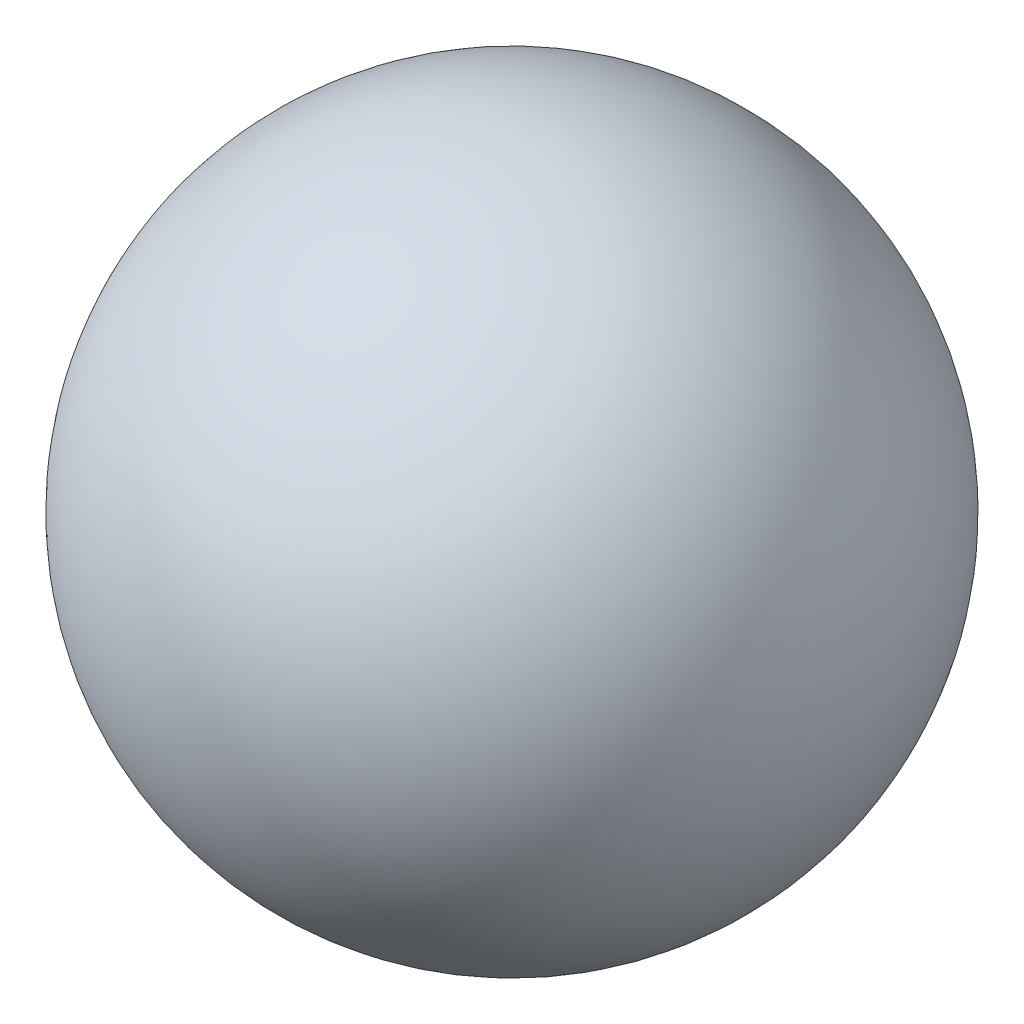
SolidWorks part; units mm, degrees
ref_plane "Front Plane" through (0, 0, 0) normal (0, 0, 1) x (1, 0, 0)
ref_plane "Top Plane" through (0, 0, 0) normal (0, 1, 0) x (1, 0, 0)
ref_plane "Right Plane" through (0, 0, 0) normal (1, 0, 0) x (0, 0, -1)
sketch "Sketch1" plane through (0, 0, 0) normal (0, 0, 1) x (1, 0, 0)
  line L0 (-19.939, 0) -> (19.939, 0) construction
  line L1 (19.939, 0) -> (-19.939, 0)
  arc A1 (19.939, 0) -> (-19.939, 0) centre (0, 0) ccw
  dimension "D1" = 19.939
revolve "Revolve7" add sketch "Sketch1" angle 360 about L0
equation "\"FoamCore\" = \".2\""
equation "\"MDF\" = \".2\""
equation "\"GMaterial\"= \".2\""
equation "\"PVCMountDiameter\" = \"0.5in\""
equation "\"PVCMountDistanceToEdge\" = \"0.5\""
equation "\"PVCThickness\" = \"0.13in\""
equation "\"BaseWidth\" = \"8in\""
equation "\"BaseLength\" = \"10in\""
equation "\"BallDiameter\" = \"1.57in\""
equation "\"BaseGap\" = \"4in\""
equation "\"FunnelTopDiameter\" = \"8in\""
equation "\"FunnelTopDepth\" = \"1.5in\""
equation "\"BallGap\" = \"0.1in\""
equation "\"FunnelLength\" = 6in"
equation "\"FunnelMaterial\" = 0.1in"
equation "\"FunnelLowerDiameter\" = \"PVCDiameter\" + \"PVCThickness\"*2"
equation "\"FunnelDepth\" = 1.5in"
equation "\"AmmoFeederLength\" = 1in + 76mm"
equation "\"AmmoFeederCutoffLength\" = \"MovingWheelDiameter\""
equation "\"D1@Sketch1\"=\"BallDiameter\"/2"
